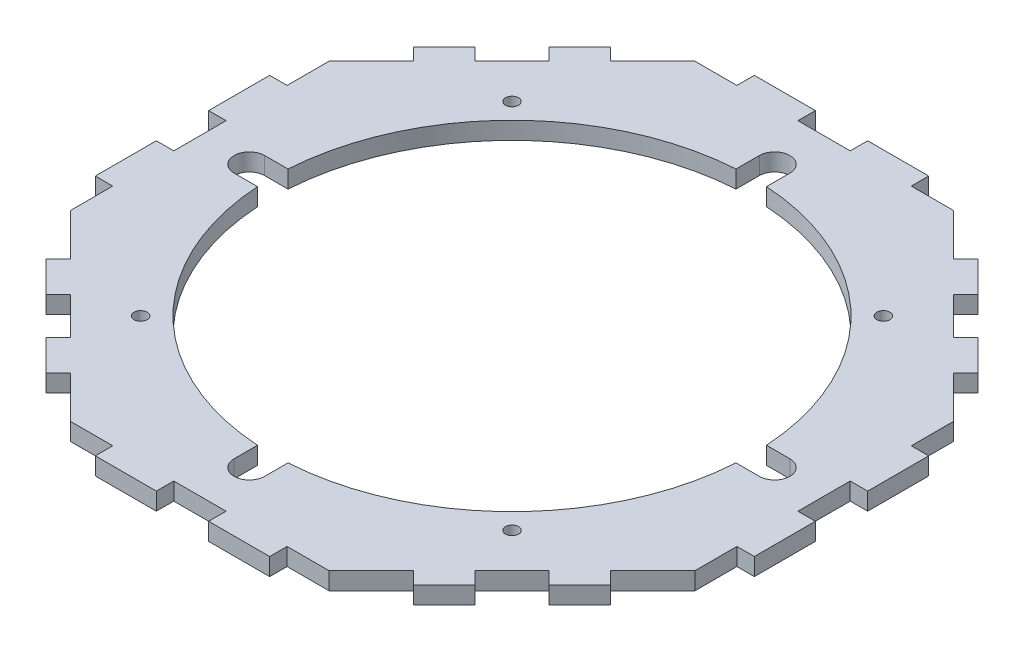
SolidWorks part; units mm, degrees
ref_plane "Front Plane" through (0, 0, 0) normal (0, 0, 1) x (1, 0, 0)
ref_plane "Top Plane" through (0, 0, 0) normal (0, 1, 0) x (1, 0, 0)
ref_plane "Right Plane" through (0, 0, 0) normal (1, 0, 0) x (0, 0, -1)
sketch "Sketch1" plane through (0, 0, 0) normal (0, 1, 0) x (1, 0, 0)
  circle A0 centre (0, 0) radius 100
  dimension "D1" = 200
extrude "Boss-Extrude1" add sketch "Sketch1" along normal blind 4
sketch "Sketch2" plane through (0, 4, 0) normal (0, 1, 0) x (1, 0, 0)
  line L4 (-32, 75.598) -> (-20, 75.598) construction
  line L5 (-20, 75.598) -> (-20, 71.598) construction
  line L6 (-20, 71.598) -> (-32, 71.598) construction
  line L7 (-32, 71.598) -> (-32, 75.598) construction
  line L96 (-42.1421, 64.7696) -> (-33.6569, 73.2548) construction
  line L113 (-33.6569, 73.2548) -> (-30.8284, 70.4264) construction
  line L114 (-30.8284, 70.4264) -> (-39.3137, 61.9411) construction
  line L115 (-39.3137, 61.9411) -> (-42.1421, 64.7696) construction
  line L116 (-57.6985, 49.2132) -> (-49.2132, 57.6985) construction
  line L117 (-49.2132, 57.6985) -> (-46.3848, 54.8701) construction
  line L118 (-46.3848, 54.8701) -> (-54.8701, 46.3848) construction
  line L119 (-54.8701, 46.3848) -> (-57.6985, 49.2132) construction
  line L120 (-73.2548, 33.6569) -> (-64.7696, 42.1421) construction
  line L121 (-64.7696, 42.1421) -> (-61.9411, 39.3137) construction
  line L122 (-61.9411, 39.3137) -> (-70.4264, 30.8284) construction
  line L123 (-70.4264, 30.8284) -> (-73.2548, 33.6569) construction
  line L124 (-75.598, 20) -> (-75.598, 32) construction
  line L125 (-75.598, 32) -> (-71.598, 32) construction
  line L126 (-71.598, 32) -> (-71.598, 20) construction
  line L127 (-71.598, 20) -> (-75.598, 20) construction
  line L128 (-75.598, -6) -> (-75.598, 6) construction
  line L129 (-75.598, 6) -> (-71.598, 6) construction
  line L130 (-71.598, 6) -> (-71.598, -6) construction
  line L131 (-71.598, -6) -> (-75.598, -6) construction
  line L132 (-75.598, -32) -> (-75.598, -20) construction
  line L133 (-75.598, -20) -> (-71.598, -20) construction
  line L134 (-71.598, -20) -> (-71.598, -32) construction
  line L135 (-71.598, -32) -> (-75.598, -32) construction
  line L136 (-64.7696, -42.1421) -> (-73.2548, -33.6569) construction
  line L137 (-73.2548, -33.6569) -> (-70.4264, -30.8284) construction
  line L138 (-70.4264, -30.8284) -> (-61.9411, -39.3137) construction
  line L139 (-61.9411, -39.3137) -> (-64.7696, -42.1421) construction
  line L140 (-49.2132, -57.6985) -> (-57.6985, -49.2132) construction
  line L141 (-57.6985, -49.2132) -> (-54.8701, -46.3848) construction
  line L142 (-54.8701, -46.3848) -> (-46.3848, -54.8701) construction
  line L143 (-46.3848, -54.8701) -> (-49.2132, -57.6985) construction
  line L144 (-33.6569, -73.2548) -> (-42.1421, -64.7696) construction
  line L145 (-42.1421, -64.7696) -> (-39.3137, -61.9411) construction
  line L146 (-39.3137, -61.9411) -> (-30.8284, -70.4264) construction
  line L147 (-30.8284, -70.4264) -> (-33.6569, -73.2548) construction
  line L148 (-32, 75.598) -> (-20, 75.598)
  line L149 (-20, 75.598) -> (-20, 71.598)
  line L150 (-20, 71.598) -> (-32, 71.598)
  line L151 (-32, 71.598) -> (-32, 75.598)
  line L152 (-42.1421, 64.7696) -> (-33.6569, 73.2548)
  line L153 (-33.6569, 73.2548) -> (-30.8284, 70.4264)
  line L154 (-30.8284, 70.4264) -> (-39.3137, 61.9411)
  line L155 (-39.3137, 61.9411) -> (-42.1421, 64.7696)
  line L156 (-57.6985, 49.2132) -> (-49.2132, 57.6985)
  line L157 (-49.2132, 57.6985) -> (-46.3848, 54.8701)
  line L158 (-46.3848, 54.8701) -> (-54.8701, 46.3848)
  line L159 (-54.8701, 46.3848) -> (-57.6985, 49.2132)
  line L160 (-73.2548, 33.6569) -> (-64.7696, 42.1421)
  line L161 (-64.7696, 42.1421) -> (-61.9411, 39.3137)
  line L162 (-61.9411, 39.3137) -> (-70.4264, 30.8284)
  line L163 (-70.4264, 30.8284) -> (-73.2548, 33.6569)
  line L164 (-75.598, 20) -> (-75.598, 32)
  line L165 (-75.598, 32) -> (-71.598, 32)
  line L166 (-71.598, 32) -> (-71.598, 20)
  line L167 (-71.598, 20) -> (-75.598, 20)
  line L168 (-75.598, -6) -> (-75.598, 6)
  line L169 (-75.598, 6) -> (-71.598, 6)
  line L170 (-71.598, 6) -> (-71.598, -6)
  line L171 (-71.598, -6) -> (-75.598, -6)
  line L172 (-75.598, -32) -> (-75.598, -20)
  line L173 (-75.598, -20) -> (-71.598, -20)
  line L174 (-71.598, -20) -> (-71.598, -32)
  line L175 (-71.598, -32) -> (-75.598, -32)
  line L176 (-64.7696, -42.1421) -> (-73.2548, -33.6569)
  line L177 (-73.2548, -33.6569) -> (-70.4264, -30.8284)
  line L178 (-70.4264, -30.8284) -> (-61.9411, -39.3137)
  line L179 (-61.9411, -39.3137) -> (-64.7696, -42.1421)
  line L180 (-49.2132, -57.6985) -> (-57.6985, -49.2132)
  line L181 (-57.6985, -49.2132) -> (-54.8701, -46.3848)
  line L182 (-54.8701, -46.3848) -> (-46.3848, -54.8701)
  line L183 (-46.3848, -54.8701) -> (-49.2132, -57.6985)
  line L184 (-33.6569, -73.2548) -> (-42.1421, -64.7696)
  line L185 (-42.1421, -64.7696) -> (-39.3137, -61.9411)
  line L186 (-39.3137, -61.9411) -> (-30.8284, -70.4264)
  line L187 (-30.8284, -70.4264) -> (-33.6569, -73.2548)
  line L188 (71.598, -6) -> (71.598, 6) construction
  line L189 (71.598, 6) -> (75.598, 6) construction
  line L190 (75.598, 6) -> (75.598, -6) construction
  line L191 (75.598, -6) -> (71.598, -6) construction
  line L192 (71.598, -32) -> (71.598, -20) construction
  line L193 (71.598, -20) -> (75.598, -20) construction
  line L194 (75.598, -20) -> (75.598, -32) construction
  line L195 (75.598, -32) -> (71.598, -32) construction
  line L196 (71.598, 20) -> (71.598, 32) construction
  line L197 (71.598, 32) -> (75.598, 32) construction
  line L198 (75.598, 32) -> (75.598, 20) construction
  line L199 (75.598, 20) -> (71.598, 20) construction
  line L200 (70.4264, 30.8284) -> (61.9411, 39.3137) construction
  line L201 (61.9411, 39.3137) -> (64.7696, 42.1421) construction
  line L202 (64.7696, 42.1421) -> (73.2548, 33.6569) construction
  line L203 (73.2548, 33.6569) -> (70.4264, 30.8284) construction
  line L204 (39.3137, 61.9411) -> (30.8284, 70.4264) construction
  line L205 (30.8284, 70.4264) -> (33.6569, 73.2548) construction
  line L206 (33.6569, 73.2548) -> (42.1421, 64.7696) construction
  line L207 (42.1421, 64.7696) -> (39.3137, 61.9411) construction
  line L208 (54.8701, 46.3848) -> (46.3848, 54.8701) construction
  line L209 (46.3848, 54.8701) -> (49.2132, 57.6985) construction
  line L210 (49.2132, 57.6985) -> (57.6985, 49.2132) construction
  line L211 (57.6985, 49.2132) -> (54.8701, 46.3848) construction
  line L212 (20, 75.598) -> (32, 75.598) construction
  line L213 (32, 75.598) -> (32, 71.598) construction
  line L214 (32, 71.598) -> (20, 71.598) construction
  line L215 (20, 71.598) -> (20, 75.598) construction
  line L216 (-6, 75.598) -> (6, 75.598) construction
  line L217 (6, 75.598) -> (6, 71.598) construction
  line L218 (6, 71.598) -> (-6, 71.598) construction
  line L219 (-6, 71.598) -> (-6, 75.598) construction
  line L220 (71.598, -6) -> (71.598, 6)
  line L221 (71.598, 6) -> (75.598, 6)
  line L222 (75.598, 6) -> (75.598, -6)
  line L223 (75.598, -6) -> (71.598, -6)
  line L224 (71.598, -32) -> (71.598, -20)
  line L225 (71.598, -20) -> (75.598, -20)
  line L226 (75.598, -20) -> (75.598, -32)
  line L227 (75.598, -32) -> (71.598, -32)
  line L228 (71.598, 20) -> (71.598, 32)
  line L229 (71.598, 32) -> (75.598, 32)
  line L230 (75.598, 32) -> (75.598, 20)
  line L231 (75.598, 20) -> (71.598, 20)
  line L232 (70.4264, 30.8284) -> (61.9411, 39.3137)
  line L233 (61.9411, 39.3137) -> (64.7696, 42.1421)
  line L234 (64.7696, 42.1421) -> (73.2548, 33.6569)
  line L235 (73.2548, 33.6569) -> (70.4264, 30.8284)
  line L236 (39.3137, 61.9411) -> (30.8284, 70.4264)
  line L237 (30.8284, 70.4264) -> (33.6569, 73.2548)
  line L238 (33.6569, 73.2548) -> (42.1421, 64.7696)
  line L239 (42.1421, 64.7696) -> (39.3137, 61.9411)
  line L240 (54.8701, 46.3848) -> (46.3848, 54.8701)
  line L241 (46.3848, 54.8701) -> (49.2132, 57.6985)
  line L242 (49.2132, 57.6985) -> (57.6985, 49.2132)
  line L243 (57.6985, 49.2132) -> (54.8701, 46.3848)
  line L244 (20, 75.598) -> (32, 75.598)
  line L245 (32, 75.598) -> (32, 71.598)
  line L246 (32, 71.598) -> (20, 71.598)
  line L247 (20, 71.598) -> (20, 75.598)
  line L248 (-6, 75.598) -> (6, 75.598)
  line L249 (6, 75.598) -> (6, 71.598)
  line L250 (6, 71.598) -> (-6, 71.598)
  line L251 (-6, 71.598) -> (-6, 75.598)
  line L252 (61.9411, -39.3137) -> (70.4264, -30.8284) construction
  line L253 (70.4264, -30.8284) -> (73.2548, -33.6569) construction
  line L254 (73.2548, -33.6569) -> (64.7696, -42.1421) construction
  line L255 (64.7696, -42.1421) -> (61.9411, -39.3137) construction
  line L256 (46.3848, -54.8701) -> (54.8701, -46.3848) construction
  line L257 (54.8701, -46.3848) -> (57.6985, -49.2132) construction
  line L258 (57.6985, -49.2132) -> (49.2132, -57.6985) construction
  line L259 (49.2132, -57.6985) -> (46.3848, -54.8701) construction
  line L260 (30.8284, -70.4264) -> (39.3137, -61.9411) construction
  line L261 (39.3137, -61.9411) -> (42.1421, -64.7696) construction
  line L262 (42.1421, -64.7696) -> (33.6569, -73.2548) construction
  line L263 (33.6569, -73.2548) -> (30.8284, -70.4264) construction
  line L264 (61.9411, -39.3137) -> (70.4264, -30.8284)
  line L265 (70.4264, -30.8284) -> (73.2548, -33.6569)
  line L266 (73.2548, -33.6569) -> (64.7696, -42.1421)
  line L267 (64.7696, -42.1421) -> (61.9411, -39.3137)
  line L268 (46.3848, -54.8701) -> (54.8701, -46.3848)
  line L269 (54.8701, -46.3848) -> (57.6985, -49.2132)
  line L270 (57.6985, -49.2132) -> (49.2132, -57.6985)
  line L271 (49.2132, -57.6985) -> (46.3848, -54.8701)
  line L272 (30.8284, -70.4264) -> (39.3137, -61.9411)
  line L273 (39.3137, -61.9411) -> (42.1421, -64.7696)
  line L274 (42.1421, -64.7696) -> (33.6569, -73.2548)
  line L275 (33.6569, -73.2548) -> (30.8284, -70.4264)
  line L276 (-70.4264, -30.8284) -> (-71.598, -29.6569)
  line L277 (-39.3137, -61.9411) -> (-61.9411, -39.3137)
  line L278 (-30.8284, 70.4264) -> (-71.598, 29.6569)
  line L279 (-30.8284, 70.4264) -> (-29.6569, 71.598)
  line L280 (71.598, 29.6569) -> (29.6569, 71.598)
  line L281 (0, 0) -> (-71.598, 0) construction
  line L282 (-32, -71.598) -> (-32, -75.598)
  line L283 (32, -75.598) -> (32, -71.598)
  line L284 (-6, -71.598) -> (-6, -75.598)
  line L285 (6, -71.598) -> (-6, -71.598)
  line L286 (6, -75.598) -> (6, -71.598)
  line L287 (-6, -75.598) -> (6, -75.598)
  line L288 (20, -71.598) -> (20, -75.598)
  line L289 (32, -71.598) -> (20, -71.598)
  line L290 (20, -75.598) -> (32, -75.598)
  line L291 (-20, -71.598) -> (-32, -71.598)
  line L292 (-20, -75.598) -> (-20, -71.598)
  line L293 (-32, -75.598) -> (-20, -75.598)
  line L294 (71.598, -29.6569) -> (29.6569, -71.598)
  line L295 (-29.6569, -71.598) -> (-30.8284, -70.4264)
  line L296 (20, -71.598) -> (-20, -71.598)
  line L297 (-71.598, -20) -> (-71.598, 20)
  line L298 (20, 71.598) -> (-20, 71.598)
  line L299 (71.598, -20) -> (71.598, 20)
extrude "Cut-Extrude1" cut sketch "Sketch2" against normal blind 4 contours L175 L174 L173 L172 | L171 L297 L170 L169 L168 | L167 L166 L165 L164 | L163 L162 L161 L160 | L159 L158 L157 L156 | L155 L154 L153 L152 | L151 L150 L149 L148 | L251 L250 L249 L248 | L247 L246 L245 L244 | L239 L238 L237 L236 | L243 L242 L241 L240 | L235 L234 L233 L232 | L223 L222 L221 L220 | L231 L230 L229 L228 | L227 L226 L225 L224 | L267 L266 L265 L264 | L224 L294 L265 | L271 L270 L269 L268 | L275 L274 L273 L272 | L275 L294 L289 | L288 L290 L283 L289 | L284 L287 L286 L285 | L282 L293 L292 L291 | L291 L295 L187 | L187 L186 L185 L184 | L183 L182 L181 L180 | L179 L178 L177 L176 | L177 L276 L174 | L278 L163 L166 | L153 L279 L150 | L280 L237 L246 | L280 L228 L235
sketch "Sketch3" plane through (0, 4, 0) normal (0, 1, 0) x (1, 0, 0)
  line L0 (-32, -75.598) -> (-75.598, -32)
  line L1 (-75.598, -32) -> (-75.598, 32)
  line L2 (-75.598, 32) -> (-32, 75.598)
  line L3 (-32, 75.598) -> (32, 75.598)
  line L4 (32, 75.598) -> (75.598, 32)
  line L5 (75.598, 32) -> (75.598, -32)
  line L6 (75.598, -32) -> (32, -75.598)
  line L7 (32, -75.598) -> (-32, -75.598)
  line L8 (-75.598, 30.6117) -> (-70.1995, 31.905)
  line L9 (-70.1995, 31.905) -> (-64.7696, 42.1421)
  line L10 (-64.7696, 42.1421) -> (-42.1421, 64.7696)
  line L11 (-42.1421, 64.7696) -> (-31.0642, 71.6656)
  line L12 (-31.0642, 71.6656) -> (-28.7887, 75.598)
  line L13 (-64.7696, -42.1421) -> (-71.2524, -31.1679)
  line L14 (-71.2524, -31.1679) -> (-75.598, -30.5486)
  line L15 (-64.7696, -42.1421) -> (-42.1421, -64.7696)
  line L16 (-42.1421, -64.7696) -> (-30.351, -72.1691)
  line L17 (-30.351, -72.1691) -> (-29.0939, -75.598)
  line L18 (27.3281, -75.598) -> (32, -70.177)
  line L19 (32, -70.177) -> (42.1421, -64.7696)
  line L20 (42.1421, -64.7696) -> (64.7696, -42.1421)
  line L21 (64.7696, -42.1421) -> (70.8388, -31.3566)
  line L22 (70.8388, -31.3566) -> (75.598, -29.5465)
  line L23 (75.598, 29.5624) -> (70.8388, 31.5318)
  line L24 (70.8388, 31.5318) -> (64.7696, 42.1421)
  line L25 (64.7696, 42.1421) -> (42.1421, 64.7696)
  line L26 (42.1421, 64.7696) -> (31.1561, 71.2581)
  line L27 (31.1561, 71.2581) -> (29.8079, 75.598)
  circle A0 centre (0, 0) radius 100 construction
  circle A1 centre (0, 0) radius 100
extrude "Cut-Extrude3" cut sketch "Sketch3" against normal blind 4 contours A1 L6 L7 L0 L1 L2 L3 L4 L5 | L11 L12 L3 L2 L1 L8 L9 L10 | L17 L16 L15 L13 L14 L1 L0 L7 | L22 L21 L20 L19 L18 L7 L6 L5 | L27 L26 L25 L24 L23 L5 L4 L3
sketch "Sketch5" plane through (0, 4, 0) normal (0, 1, 0) x (1, 0, 0)
  circle A0 centre (0, 0) radius 55
  dimension "D1" = 110
extrude "Cut-Extrude4" cut sketch "Sketch5" against normal through all
sketch "Sketch6" plane through (0, 4, 0) normal (0, 1, 0) x (1, 0, 0)
  circle A0 centre (-60.25, 0) radius 1.5
  dimension "D1" = 3
extrude "Cut-Extrude5" cut sketch "Sketch6" against normal through all
pattern_circular "CirPattern1" count 8 over 360 about axis through (0, 0, 0) along (0, 1, 0) of "Cut-Extrude5"
sketch "Sketch7" plane through (0, 4, 0) normal (0, 1, 0) x (1, 0, 0)
  line L0 (-3.5, 60.25) -> (-3.5, 54.8885)
  line L1 (3.5, 60.25) -> (3.5, 54.8885)
  circle A0 centre (0, 60.25) radius 3.5
  circle A1 centre (0, 0) radius 55 construction
  circle A2 centre (0, 0) radius 55
  point P5 (3.1, 54.9126)
  dimension "D1" = 7
extrude "Cut-Extrude6" cut sketch "Sketch7" against normal blind 10 contours A2 L1 A0 L0 | A0
pattern_circular "CirPattern2" count 4 over 360 about axis through (0, 0, 0) along (0, 1, 0) of "Cut-Extrude6"
sketch "Sketch8" plane through (0, 4, 0) normal (0, 1, 0) x (1, 0, 0)
  line L0 (-29.6569, 71.598) -> (29.6569, -71.598)
  line L1 (33.4848, -80.8395) -> (-33.4848, 80.8395)
  circle A0 centre (0, 0) radius 87.5
  point P9 (0, 0)
  dimension "D1" = 175
